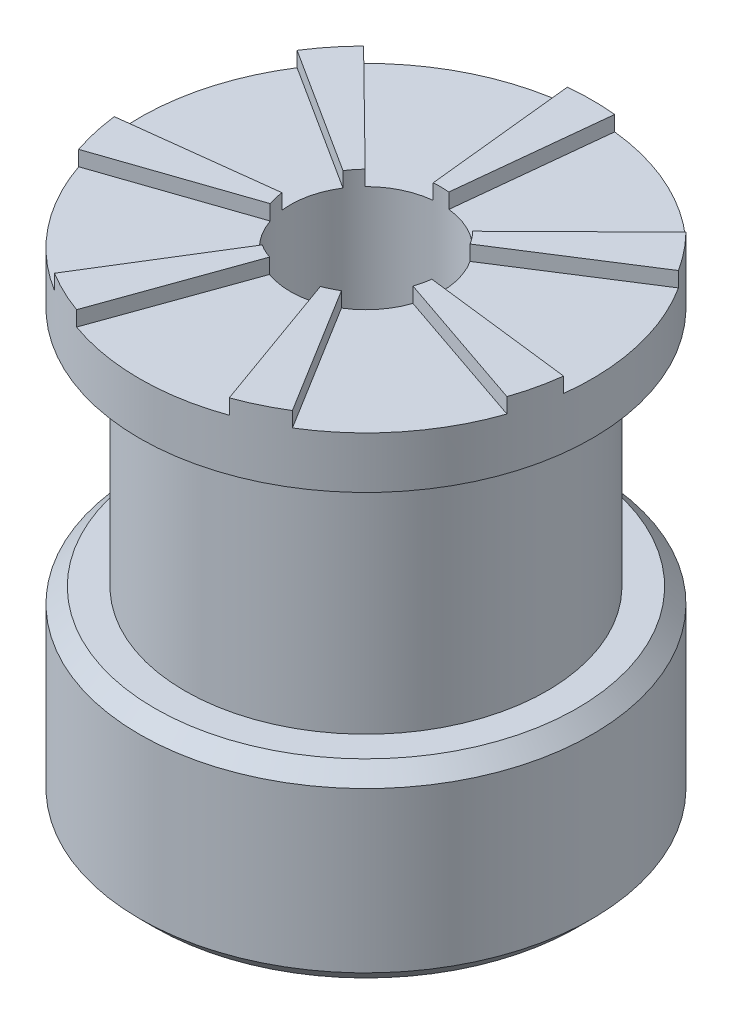
SolidWorks part; units mm, degrees
material "AISI 1010 Steel, hot rolled bar"
ref_plane "Front Plane" through (0, 0, 0) normal (0, 0, 1) x (1, 0, 0)
ref_plane "Top Plane" through (0, 0, 0) normal (0, 1, 0) x (1, 0, 0)
ref_plane "Right Plane" through (0, 0, 0) normal (1, 0, 0) x (0, 0, -1)
sketch "Sketch2" plane through (0, 0, 0) normal (0, 1, 0) x (1, 0, 0)
  circle A0 centre (0, 0) radius 7.5
  circle A1 centre (0, 0) radius 2.5
  dimension "D1" = 15
  dimension "D2" = 5
extrude "Boss-Extrude1" add sketch "Sketch2" along normal blind 16
ref_plane "Plane1" through (0, 6.29, 0) normal (0, 1, 0) x (1, 0, 0)
sketch "Sketch3" plane through (0, 6.29, 0) normal (0, 1, 0) x (1, 0, 0)
  circle A43 centre (0, 0) radius 6
  dimension "D1" = 12
extrude "Cut-Extrude1" cut sketch "Sketch3" along normal blind 8 flip side to cut
chamfer "Chamfer1" distance 0.5 angle 45 2 edges at (0, 0, 7.5) (0, 6.29, 7.5)
sketch "Sketch7" plane through (0, 16, 0) normal (0, 1, 0) x (1, 0, 0)
  line L0 (0, 7.5) -> (0, 2.5) construction
  line L1 (0.784, 7.4589) -> (0.2613, 2.4863)
  line L2 (-0.784, 7.4589) -> (-0.2613, 2.4863)
  line L3 (5.3428, 5.2635) -> (1.7809, 1.7545)
  line L4 (6.3204, 4.0376) -> (2.1068, 1.3459)
  line L5 (7.4464, -0.8955) -> (2.4821, -0.2985)
  line L6 (7.0975, -2.4241) -> (2.3658, -0.808)
  line L7 (3.9426, -6.3801) -> (1.3142, -2.1267)
  line L8 (2.53, -7.0604) -> (0.8433, -2.3535)
  line L9 (-2.53, -7.0604) -> (-0.8433, -2.3535)
  line L10 (-3.9426, -6.3801) -> (-1.3142, -2.1267)
  line L11 (-7.0975, -2.4241) -> (-2.3658, -0.808)
  line L12 (-7.4464, -0.8955) -> (-2.4821, -0.2985)
  line L13 (-6.3204, 4.0376) -> (-2.1068, 1.3459)
  line L14 (-5.3428, 5.2635) -> (-1.7809, 1.7545)
  circle A0 centre (0, 0) radius 7.5 construction
  arc A1 (0.784, 7.4589) -> (-0.784, 7.4589) centre (0, 0) ccw
  arc A2 (6.3204, 4.0376) -> (5.3428, 5.2635) centre (0, 0) ccw
  arc A3 (7.0975, -2.4241) -> (7.4464, -0.8955) centre (0, 0) ccw
  arc A4 (2.53, -7.0604) -> (3.9426, -6.3801) centre (0, 0) ccw
  arc A5 (-3.9426, -6.3801) -> (-2.53, -7.0604) centre (0, 0) ccw
  arc A6 (-7.4464, -0.8955) -> (-7.0975, -2.4241) centre (0, 0) ccw
  arc A7 (-5.3428, 5.2635) -> (-6.3204, 4.0376) centre (0, 0) ccw
  circle A8 centre (0, 0) radius 2.5
  point P21 (0, 0)
  circle M5 centre (0, 0) radius 7.5
  circle M6 centre (0, 0) radius 2.5
  dimension "D3" = 5
  dimension "D1" = 6
  dimension "D2" = 7
extrude "Boss-Extrude2" add sketch "Sketch7" along normal blind 0.5 contours L0 A8 L1 M5 | L0 A1 L2 M6 | L14 L13 M5 M6 | L12 L11 M5 M6 | L10 L9 M5 M6 | L8 L7 M5 M6 | L6 L5 M5 M6 | L4 L3 M5 M6
